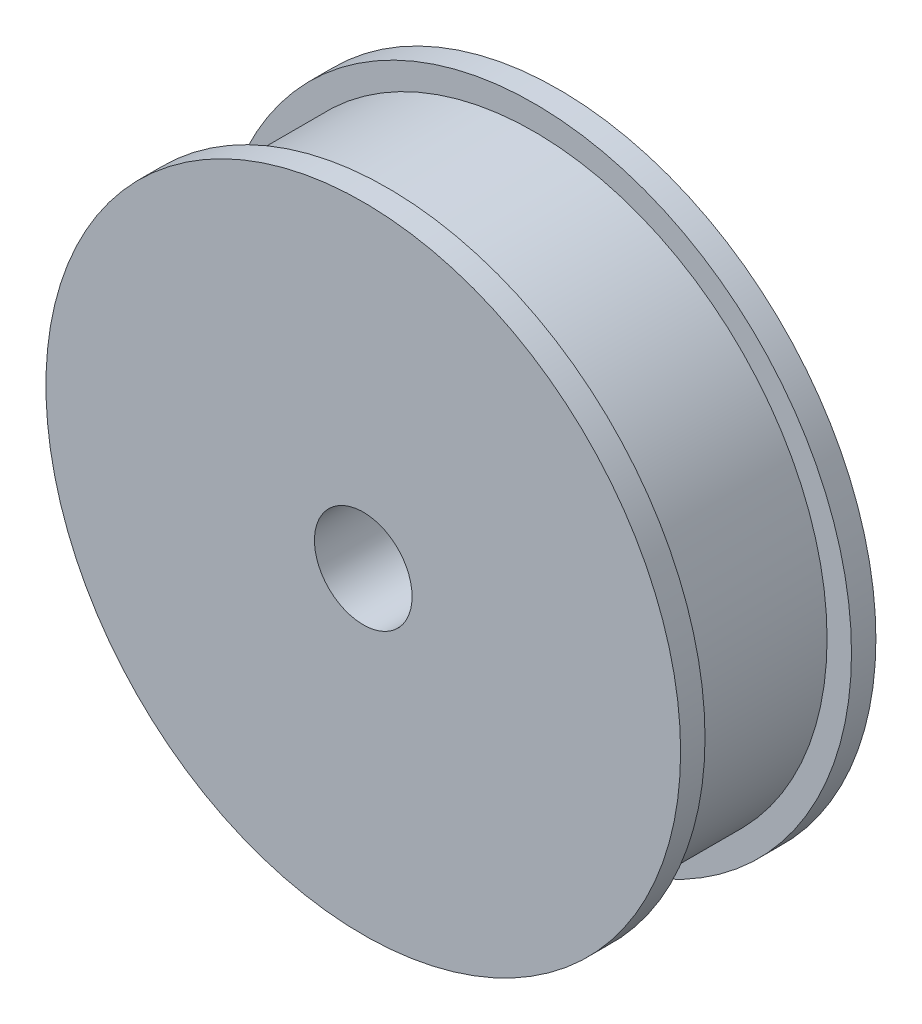
SolidWorks part; units mm, degrees
ref_plane "前视" through (0, 0, 0) normal (0, 0, 1) x (1, 0, 0)
ref_plane "上视" through (0, 0, 0) normal (0, 1, 0) x (1, 0, 0)
ref_plane "右视" through (0, 0, 0) normal (1, 0, 0) x (0, 0, -1)
sketch "草图1" plane through (0, 0, 0) normal (0, 0, 1) x (1, 0, 0)
  circle A0 centre (0, 0) radius 19.5
  dimension "D1" = 39
extrude "凸台-拉伸1" add sketch "草图1" along normal blind 12
ref_plane "基准面1" through (0, 0, 6) normal (0, 0, 1) x (1, 0, 0)
sketch "草图2" plane through (0, 0, 6) normal (0, 0, 1) x (1, 0, 0)
  circle A0 centre (0, 0) radius 18
  circle A1 centre (0, 0) radius 19.5
  dimension "D1" = 36
  dimension "D2" = 39
extrude "切除-拉伸1" cut sketch "草图2" against normal blind 4.5 and the other way blind 4.5
sketch "草图3" plane through (0, 0, 12) normal (0, 0, 1) x (1, 0, 0)
  circle A0 centre (0, 0) radius 3
  dimension "D1" = 6
extrude "切除-拉伸2" cut sketch "草图3" against normal through all
